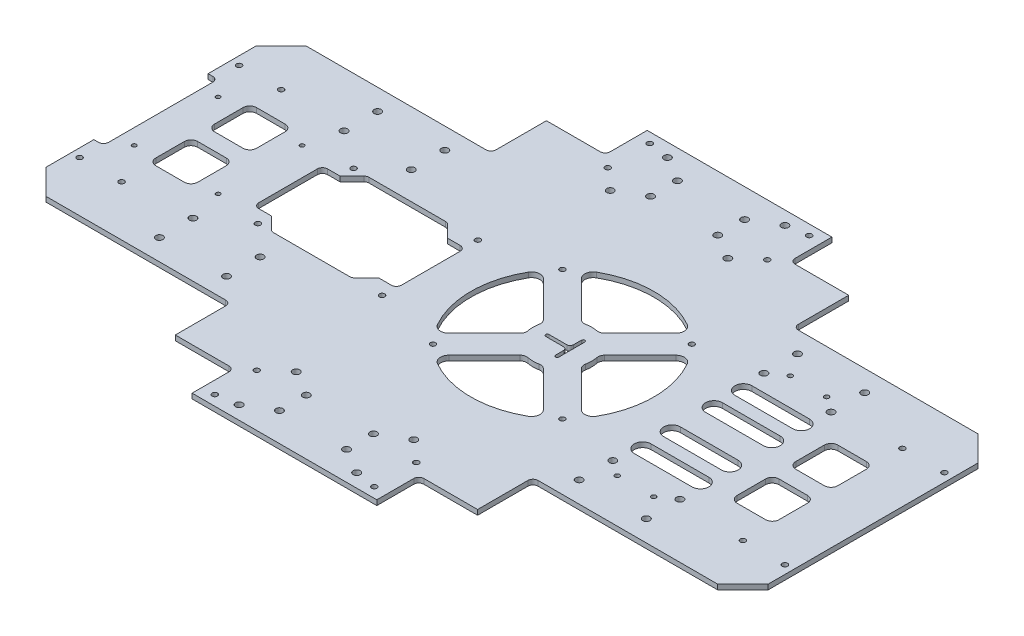
SolidWorks part; units mm, degrees
ref_plane "前视基准面" through (0, 0, 0) normal (0, 0, 1) x (1, 0, 0)
ref_plane "上视基准面" through (0, 0, 0) normal (0, 1, 0) x (1, 0, 0)
ref_plane "右视基准面" through (0, 0, 0) normal (1, 0, 0) x (0, 0, -1)
sketch "草图1" plane through (0, 0, 0) normal (0, 1, 0) x (1, 0, 0)
  line L0 (-82.9301, 135.4999) -> (-82.9301, 112.4999)
  line L1 (77.0699, 77.4999) -> (77.0699, -77.4999)
  line L2 (-47.9301, 77.4999) -> (77.0699, 77.4999)
  line L3 (-137.9301, 0) -> (-352.9301, 0) construction
  line L4 (-47.9301, -77.4999) -> (77.0699, -77.4999)
  line L5 (-137.9301, 112.4999) -> (-137.9301, -112.4999) construction
  line L6 (-137.9301, 0) -> (77.0699, 0) construction
  line L7 (-227.9301, -77.4999) -> (-352.9301, -77.4999)
  line L8 (-82.9301, 135.4999) -> (-192.9301, 135.4999)
  line L9 (-192.9301, 135.4999) -> (-192.9301, 112.4999)
  line L10 (-192.9301, -135.4999) -> (-82.9301, -135.4999)
  line L11 (-82.9301, -135.4999) -> (-82.9301, -112.4999)
  line L12 (-47.9301, 112.4999) -> (-47.9301, 77.4999)
  line L13 (-227.9301, 77.4999) -> (-352.9301, 77.4999)
  line L14 (-352.9301, 77.4999) -> (-352.9301, -77.4999)
  line L15 (-192.9301, -112.4999) -> (-192.9301, -135.4999)
  line L16 (-47.9301, -112.4999) -> (-82.9301, -112.4999)
  line L17 (-47.9301, 112.4999) -> (-82.9301, 112.4999)
  line L18 (-47.9301, -112.4999) -> (-47.9301, -77.4999)
  line L19 (-227.9301, -112.4999) -> (-227.9301, -77.4999)
  line L20 (-227.9301, -112.4999) -> (-192.9301, -112.4999)
  line L21 (-227.9301, 112.4999) -> (-192.9301, 112.4999)
  line L22 (-227.9301, 112.4999) -> (-227.9301, 77.4999)
  point P7 (77.0699, 0)
extrude "凸台-拉伸1" add sketch "草图1" along normal blind 3
fillet "圆角1" radius 3 8 edges at (-227.9301, 1.5, -77.4999) (-192.9301, 1.5, -112.4999) (-227.9301, 1.5, 77.4999) (-192.9301, 1.5, 112.4999) (-82.9301, 1.5, 112.4999) (-47.9301, 1.5, 77.4999) (-47.9301, 1.5, -77.4999) (-82.9301, 1.5, -112.4999)
sketch "草图2" plane through (0, 3, 0) normal (0, 1, 0) x (1, 0, 0)
  line L0 (77.0699, 47.5) -> (72.0699, 47.5) construction
  line L1 (72.0699, 47.5) -> (47.0699, 47.5) construction
  line L2 (47.0699, 47.5) -> (47.0699, -47.5) construction
  line L3 (47.0699, -47.5) -> (72.0699, -47.5) construction
  line L4 (72.0699, -47.5) -> (72.0699, 47.5) construction
  line L5 (72.0699, -47.5) -> (77.0699, -47.5) construction
  line L6 (77.0699, 0) -> (-352.9301, 0) construction
  line L7 (77.0699, -77.4999) -> (77.0699, 77.4999) construction
  line L8 (-352.9301, 77.4999) -> (-352.9301, -77.4999) construction
  line L9 (77.0699, 47.5) -> (77.0699, -47.5) construction
  line L10 (-137.9301, 135.4999) -> (-137.9301, -135.4999) construction
  line L11 (-82.9301, 135.4999) -> (-192.9301, 135.4999) construction
  line L12 (-192.9301, -135.4999) -> (-82.9301, -135.4999) construction
  line L13 (-90.4301, 104.4999) -> (-90.4301, 129.4999) construction
  line L14 (-90.4301, 129.4999) -> (-90.4301, 135.4999) construction
  line L15 (-185.4301, 135.4999) -> (-185.4301, 129.4999) construction
  line L16 (-185.4301, 104.4999) -> (-90.4301, 104.4999) construction
  line L17 (-185.4301, 135.4999) -> (-90.4301, 135.4999) construction
  line L18 (-185.4301, 129.4999) -> (-185.4301, 104.4999) construction
  line L19 (-90.4301, 129.4999) -> (-185.4301, 129.4999) construction
  line L20 (-90.4301, -129.4999) -> (-185.4301, -129.4999) construction
  line L21 (-185.4301, -129.4999) -> (-185.4301, -104.4999) construction
  line L22 (-185.4301, -135.4999) -> (-90.4301, -135.4999) construction
  line L23 (-185.4301, -104.4999) -> (-90.4301, -104.4999) construction
  line L24 (-185.4301, -135.4999) -> (-185.4301, -129.4999) construction
  line L25 (-90.4301, -129.4999) -> (-90.4301, -135.4999) construction
  line L26 (-90.4301, -104.4999) -> (-90.4301, -129.4999) construction
  line L27 (-352.9301, 47.5) -> (-352.9301, -47.5) construction
  line L28 (-347.9301, -47.5) -> (-352.9301, -47.5) construction
  line L29 (-347.9301, -47.5) -> (-347.9301, 47.5) construction
  line L30 (-322.9301, -47.5) -> (-347.9301, -47.5) construction
  line L31 (-322.9301, 47.5) -> (-322.9301, -47.5) construction
  line L32 (-347.9301, 47.5) -> (-322.9301, 47.5) construction
  line L33 (-352.9301, 47.5) -> (-347.9301, 47.5) construction
  circle A0 centre (47.0699, 47.5) radius 1.6
  circle A1 centre (72.0699, 47.5) radius 1.6
  circle A2 centre (47.0699, -47.5) radius 1.6
  circle A3 centre (72.0699, -47.5) radius 1.6
  circle A4 centre (-185.4301, 104.4999) radius 1.6
  circle A5 centre (-90.4301, 129.4999) radius 1.6
  circle A6 centre (-90.4301, 104.4999) radius 1.6
  circle A7 centre (-185.4301, 129.4999) radius 1.6
  circle A8 centre (-185.4301, -129.4999) radius 1.6
  circle A9 centre (-90.4301, -104.4999) radius 1.6
  circle A10 centre (-90.4301, -129.4999) radius 1.6
  circle A11 centre (-185.4301, -104.4999) radius 1.6
  circle A12 centre (-347.9301, -47.5) radius 1.6
  circle A13 centre (-322.9301, -47.5) radius 1.6
  circle A14 centre (-347.9301, 47.5) radius 1.6
  circle A15 centre (-322.9301, 47.5) radius 1.6
extrude "切除-拉伸1" cut sketch "草图2" against normal blind 47
sketch "草图3" plane through (0, 3, 0) normal (0, 1, 0) x (1, 0, 0)
  line L0 (-137.9301, 135.4999) -> (-137.9301, -135.4999) construction
  line L1 (-82.9301, 135.4999) -> (-192.9301, 135.4999) construction
  line L2 (-192.9301, -135.4999) -> (-82.9301, -135.4999) construction
  line L3 (-137.9301, 0) -> (-262.9301, 0) construction
  line L4 (-137.9301, 0) -> (-12.9301, 0) construction
  line L5 (-262.9301, 0) -> (-262.9301, 55) construction
  line L6 (-12.9301, -34) -> (-12.9301, 34) construction
  line L7 (-12.9301, 0) -> (-12.9301, 62) construction
  line L8 (-12.9301, 0) -> (-12.9301, -62) construction
  line L9 (-282.9301, -45) -> (-242.9301, -65) construction
  line L10 (-282.9301, 65) -> (-242.9301, 65) construction
  line L11 (-282.9301, 65) -> (-282.9301, 45) construction
  line L12 (-282.9301, 45) -> (-242.9301, 45) construction
  line L13 (-242.9301, 65) -> (-242.9301, 45) construction
  line L14 (-282.9301, 65) -> (-242.9301, 45) construction
  line L15 (-282.9301, 45) -> (-242.9301, 65) construction
  line L16 (-282.9301, -65) -> (-242.9301, -45) construction
  line L17 (-242.9301, -65) -> (-242.9301, -45) construction
  line L18 (-282.9301, -45) -> (-242.9301, -45) construction
  line L19 (-282.9301, -65) -> (-282.9301, -45) construction
  line L20 (-282.9301, -65) -> (-242.9301, -65) construction
  line L21 (7.0699, -65) -> (-32.9301, -65) construction
  line L22 (7.0699, -65) -> (7.0699, -45) construction
  line L23 (7.0699, -45) -> (-32.9301, -45) construction
  line L24 (-32.9301, -65) -> (-32.9301, -45) construction
  line L25 (7.0699, -65) -> (-32.9301, -45) construction
  line L26 (7.0699, 45) -> (-32.9301, 65) construction
  line L27 (7.0699, 65) -> (-32.9301, 45) construction
  line L28 (-32.9301, 65) -> (-32.9301, 45) construction
  line L29 (7.0699, 45) -> (-32.9301, 45) construction
  line L30 (7.0699, 65) -> (7.0699, 45) construction
  line L31 (7.0699, 65) -> (-32.9301, 65) construction
  line L32 (7.0699, -45) -> (-32.9301, -65) construction
  line L33 (-12.9301, 0) -> (-12.9301, -62) construction
  line L34 (-12.9301, 0) -> (-12.9301, 55) construction
  line L35 (-337.9301, 25) -> (-337.9301, -25) construction
  line L36 (-23.767, 51.5) -> (-12.9301, 34) construction
  line L37 (-352.9301, 77.4999) -> (-352.9301, -77.4999) construction
  line L38 (-23.767, 51.5) -> (-2.0931, 51.5) construction
  line L39 (-12.9301, 34) -> (-2.0931, 51.5) construction
  line L40 (-12.9301, -34) -> (-23.767, -51.5) construction
  line L41 (-23.767, -51.5) -> (-2.0931, -51.5) construction
  line L42 (-2.0931, -51.5) -> (-12.9301, -34) construction
  line L43 (-30.1258, 30) -> (4.2656, 30) construction
  line L44 (-30.1258, 35) -> (4.2656, 35)
  line L45 (-30.1258, 25) -> (-12.9301, 25)
  line L46 (-30.1258, 12.5) -> (4.2656, 12.5) construction
  line L47 (-30.1258, 17.5) -> (4.2656, 17.5)
  line L48 (-30.1258, 7.5) -> (4.2656, 7.5)
  line L49 (-30.1258, -30) -> (4.2656, -30) construction
  line L50 (-30.1258, -35) -> (4.2656, -35)
  line L51 (-30.1258, -25) -> (4.2656, -25)
  line L52 (-30.1258, -12.5) -> (4.2656, -12.5) construction
  line L53 (-30.1258, -17.5) -> (4.2656, -17.5)
  line L54 (-30.1258, -7.5) -> (4.2656, -7.5)
  line L55 (-8.9301, 25) -> (4.2656, 25)
  line L57 (-12.9301, 25) -> (-8.9301, 25)
  line L60 (-16.9301, -35) -> (-8.9301, 35) construction
  line L61 (-16.9301, 35) -> (-8.9301, -35) construction
  circle A0 centre (-282.9301, 65) radius 2.1
  circle A1 centre (-282.9301, 45) radius 2.1
  circle A2 centre (-242.9301, 65) radius 2.1
  circle A3 centre (-242.9301, 45) radius 2.1
  circle A4 centre (-242.9301, -45) radius 2.1
  circle A5 centre (-242.9301, -65) radius 2.1
  circle A6 centre (-282.9301, -45) radius 2.1
  circle A7 centre (-282.9301, -65) radius 2.1
  circle A8 centre (7.0699, -65) radius 2.1
  circle A9 centre (7.0699, -45) radius 2.1
  circle A10 centre (-32.9301, -65) radius 2.1
  circle A11 centre (-32.9301, -45) radius 2.1
  circle A12 centre (-32.9301, 45) radius 2.1
  circle A13 centre (-32.9301, 65) radius 2.1
  circle A14 centre (7.0699, 45) radius 2.1
  circle A15 centre (7.0699, 65) radius 2.1
  circle A16 centre (-23.767, -51.5) radius 1.4
  circle A17 centre (-2.0931, -51.5) radius 1.4
  arc A18 (-30.1258, 35) -> (-30.1258, 25) centre (-30.1258, 30) ccw
  circle A19 centre (-23.767, 51.5) radius 1.4
  arc A20 (4.2656, 25) -> (4.2656, 35) centre (4.2656, 30) ccw
  circle A21 centre (-2.0931, 51.5) radius 1.4
  circle A22 centre (-337.9301, 25) radius 1.25
  circle A23 centre (-287.9301, 25) radius 1.25
  circle A24 centre (-287.9301, -25) radius 1.25
  circle A25 centre (-337.9301, -25) radius 1.25
  arc A26 (-30.1258, 17.5) -> (-30.1258, 7.5) centre (-30.1258, 12.5) ccw
  arc A27 (4.2656, 7.5) -> (4.2656, 17.5) centre (4.2656, 12.5) ccw
  arc A28 (-30.1258, -35) -> (-30.1258, -25) centre (-30.1258, -30) cw
  arc A29 (4.2656, -25) -> (4.2656, -35) centre (4.2656, -30) cw
  arc A30 (-30.1258, -17.5) -> (-30.1258, -7.5) centre (-30.1258, -12.5) cw
  arc A31 (4.2656, -7.5) -> (4.2656, -17.5) centre (4.2656, -12.5) cw
  point P66 (-352.9301, 0)
  point P68 (-12.9301, 30)
  point P76 (-12.9301, 12.5)
  point P83 (-12.9301, -30)
  point P90 (-12.9301, -12.5)
  dimension "D9" = 15
  dimension "D11" = 5
  dimension "D1" = 125
  dimension "D2" = 50
  dimension "D3" = 55
  dimension "D4" = 50
  dimension "D5" = 50
  dimension "D6" = 50
  dimension "D7" = 40
  dimension "D8" = 20
  dimension "D10" = 0
  dimension "D12" = 30
  dimension "D13" = 7.5
  dimension "D14" = 34.3914
extrude "切除-拉伸2" cut sketch "草图3" against normal blind 47
chamfer "倒角1" distance 15 angle 45 4 edges at (77.0699, 1.5, -77.4999) (77.0699, 1.5, 77.4999) (-352.9301, 1.5, 77.4999) (-352.9301, 1.5, -77.4999)
sketch "草图5" plane through (0, 3, 0) normal (0, 1, 0) x (1, 0, 0)
  line L0 (-68.5001, 28.1163) -> (-89.6587, 6.9576)
  line L1 (-89.6587, -6.9576) -> (-68.5001, -28.1163)
  line L2 (-79.8138, -39.43) -> (-100.9725, -18.2713)
  line L3 (-114.8877, -18.2713) -> (-136.0464, -39.43)
  line L4 (-147.3601, -28.1163) -> (-126.2014, -6.9576)
  line L5 (-126.2014, 6.9576) -> (-147.3601, 28.1163)
  line L6 (-136.0464, 39.43) -> (-114.8877, 18.2713)
  line L7 (-100.9725, 18.2713) -> (-79.8138, 39.43)
  line L8 (-102.3298, -7.7031) -> (-102.3298, 7.7679)
  line L9 (-104.3298, -2.9676) -> (-104.3298, -7.7031)
  line L10 (-104.3298, 7.7679) -> (-104.3298, 3.0324)
  line L11 (-116.9301, -0.9676) -> (-106.3298, -0.9676)
  line L12 (-106.3298, 1.0324) -> (-116.9301, 1.0324)
  line L13 (-352.9301, 0) -> (77.0699, 0) construction
  line L14 (-352.9301, 62.4999) -> (-352.9301, -62.4999) construction
  line L15 (77.0699, -62.4999) -> (77.0699, 62.4999) construction
  line L16 (-137.9301, -135.4999) -> (-137.9301, -67.6391) construction
  line L17 (-192.9301, -135.4999) -> (-82.9301, -135.4999) construction
  line L18 (-137.9301, -67.6391) -> (-107.9301, -67.6391) construction
  line L19 (-107.9301, -67.6391) -> (-107.9301, 0) construction
  circle A0 centre (-69.3928, 38.5373) radius 1.55
  circle A1 centre (-69.3928, -38.5373) radius 1.55
  circle A2 centre (-146.4674, -38.5373) radius 1.55
  circle A3 centre (-146.4674, 38.5373) radius 1.55
  arc A4 (-60.6246, -27.0637) -> (-60.6246, 27.0637) centre (-107.9301, 0) ccw
  arc A5 (-60.6246, 27.0637) -> (-68.5001, 28.1163) centre (-64.9645, 24.5808) ccw
  arc A6 (-89.6587, 6.9576) -> (-90.7559, 3.361) centre (-86.8303, 4.1292) ccw
  arc A7 (-90.7559, -3.361) -> (-90.7559, 3.361) centre (-107.9301, 0) ccw
  arc A8 (-90.7559, -3.361) -> (-89.6587, -6.9576) centre (-86.8303, -4.1292) ccw
  arc A9 (-68.5001, -28.1163) -> (-60.6246, -27.0637) centre (-64.9645, -24.5808) ccw
  arc A10 (-80.8664, -47.3055) -> (-79.8138, -39.43) centre (-83.3493, -42.9655) ccw
  arc A11 (-134.9937, -47.3055) -> (-80.8664, -47.3055) centre (-107.9301, 0) ccw
  arc A12 (-100.9725, -18.2713) -> (-104.5691, -17.1742) centre (-103.8009, -21.0998) ccw
  arc A13 (-111.291, -17.1742) -> (-104.5691, -17.1742) centre (-107.9301, 0) ccw
  arc A14 (-111.291, -17.1742) -> (-114.8877, -18.2713) centre (-112.0593, -21.0998) ccw
  arc A15 (-136.0464, -39.43) -> (-134.9937, -47.3055) centre (-132.5108, -42.9655) ccw
  arc A16 (-126.2014, -6.9576) -> (-125.1043, -3.361) centre (-129.0298, -4.1292) ccw
  arc A17 (-125.1043, 3.361) -> (-125.1043, -3.361) centre (-107.9301, 0) ccw
  arc A18 (-125.1043, 3.361) -> (-126.2014, 6.9576) centre (-129.0298, 4.1292) ccw
  arc A19 (-147.3601, 28.1163) -> (-155.2356, 27.0637) centre (-150.8956, 24.5808) ccw
  arc A20 (-155.2356, 27.0637) -> (-155.2356, -27.0637) centre (-107.9301, 0) ccw
  arc A21 (-155.2356, -27.0637) -> (-147.3601, -28.1163) centre (-150.8956, -24.5808) ccw
  arc A22 (-104.5691, 17.1742) -> (-111.291, 17.1742) centre (-107.9301, 0) ccw
  arc A23 (-114.8877, 18.2713) -> (-111.291, 17.1742) centre (-112.0593, 21.0998) ccw
  arc A24 (-104.5691, 17.1742) -> (-100.9725, 18.2713) centre (-103.8009, 21.0998) ccw
  arc A25 (-79.8138, 39.43) -> (-80.8664, 47.3055) centre (-83.3493, 42.9655) ccw
  arc A26 (-80.8664, 47.3055) -> (-134.9937, 47.3055) centre (-107.9301, 0) ccw
  arc A27 (-134.9937, 47.3055) -> (-136.0464, 39.43) centre (-132.5108, 42.9655) ccw
  arc A28 (-102.3298, 7.7679) -> (-104.3298, 7.7679) centre (-103.3298, 7.7679) ccw
  arc A29 (-104.3298, -7.7031) -> (-102.3298, -7.7031) centre (-103.3298, -7.7031) ccw
  arc A30 (-106.3298, 1.0324) -> (-104.3298, 3.0324) centre (-106.3298, 3.0324) ccw
  arc A31 (-104.3298, -2.9676) -> (-106.3298, -0.9676) centre (-106.3298, -2.9676) ccw
  arc A32 (-116.9301, 1.0324) -> (-116.9301, -0.9676) centre (-116.9301, 0.0324) ccw
extrude "切除-拉伸3" cut sketch "草图5" against normal blind 47
sketch "草图6" plane through (0, 3, 0) normal (0, 1, 0) x (1, 0, 0)
  line L0 (-260.7825, 28.5) -> (-186.7825, 28.5) construction
  line L1 (-260.7825, 28.5) -> (-260.7825, -28.5) construction
  line L2 (-260.7825, -28.5) -> (-186.7825, -28.5) construction
  line L3 (-186.7825, 28.5) -> (-186.7825, -28.5) construction
  line L4 (-352.9301, 0) -> (77.0699, 0) construction
  line L5 (-352.9301, 62.4999) -> (-352.9301, -62.4999) construction
  line L6 (77.0699, -62.4999) -> (77.0699, 62.4999) construction
  line L7 (-270.2825, -20.5) -> (-260.7825, -20.5)
  line L8 (-186.2825, -19.5) -> (-186.2825, 19.5)
  line L9 (-187.2825, 20.5) -> (-196.7825, 20.5)
  line L10 (-271.2825, 19.5) -> (-271.2825, -19.5)
  line L11 (-251.2825, -28.5) -> (-251.2825, -24.9) construction
  line L12 (-251.2825, -24.9) -> (-213.2825, -24.9) construction
  line L13 (-213.2825, -24.9) -> (-213.2825, -23.5) construction
  line L14 (-213.2825, -23.5) -> (-193.2825, -23.5) construction
  line L15 (-190.2825, -26.5) -> (-190.2825, -28.5) construction
  line L16 (-183.2825, -28.5) -> (-183.2825, 28.5) construction
  line L17 (-190.2825, 28.5) -> (-190.2825, 26.5) construction
  line L18 (-193.2825, 23.5) -> (-213.2825, 23.5) construction
  line L19 (-213.2825, 23.5) -> (-213.2825, 24.9) construction
  line L20 (-213.2825, 24.9) -> (-251.2825, 24.9) construction
  line L21 (-251.2825, 24.9) -> (-251.2825, 28.5) construction
  line L22 (-251.2825, 28.5) -> (-253.9086, 28.5) construction
  line L23 (-264.2825, 28.5) -> (-264.2825, 27.5) construction
  line L24 (-268.2825, 23.5) -> (-274.2825, 23.5) construction
  line L25 (-274.2825, 23.5) -> (-274.2825, -23.5) construction
  line L26 (-274.2825, -23.5) -> (-268.2825, -23.5) construction
  line L27 (-264.2825, -27.5) -> (-264.2825, -28.5) construction
  line L28 (-253.9086, -28.5) -> (-251.2825, -28.5) construction
  line L29 (-270.2825, 20.5) -> (-271.2825, 20.5)
  line L30 (-271.2825, 20.5) -> (-271.2825, 19.5)
  line L31 (-271.2825, -19.5) -> (-271.2825, -20.5)
  line L32 (-271.2825, -20.5) -> (-270.2825, -20.5)
  line L33 (-187.2825, -20.5) -> (-186.2825, -20.5)
  line L34 (-186.2825, -20.5) -> (-186.2825, -19.5)
  line L35 (-187.2825, 20.5) -> (-186.2825, 20.5)
  line L36 (-186.2825, 20.5) -> (-186.2825, 19.5)
  line L37 (-162.4301, 0) -> (-183.2825, 0) construction
  line L38 (-183.2825, 0) -> (-183.2825, 23.5) construction
  line L39 (-228.7825, 20.5) -> (-228.7825, 28.5) construction
  line L40 (-252.7825, 28.5) -> (-204.7825, 28.5)
  line L41 (-204.7825, 28.5) -> (-196.7825, 20.5)
  line L42 (-252.7825, 28.5) -> (-260.7825, 20.5)
  line L43 (-260.7825, 20.5) -> (-270.2825, 20.5)
  line L44 (-252.7825, -28.5) -> (-260.7825, -20.5)
  line L45 (-252.7825, -28.5) -> (-204.7825, -28.5)
  line L46 (-204.7825, -28.5) -> (-196.7825, -20.5)
  line L47 (-196.7825, -20.5) -> (-187.2825, -20.5)
  circle A0 centre (-260.7825, 28.5) radius 1.6
  circle A1 centre (-186.7825, 28.5) radius 1.6
  circle A2 centre (-260.7825, -28.5) radius 1.6
  circle A3 centre (-186.7825, -28.5) radius 1.6
  circle A4 centre (-186.7825, -28.5) radius 1.5 construction
  arc A5 (-190.2825, -26.5) -> (-193.2825, -23.5) centre (-193.2825, -26.5) ccw construction
  arc A6 (-190.2825, -28.5) -> (-183.2825, -28.5) centre (-186.7825, -28.5) ccw construction
  arc A7 (-183.2825, 28.5) -> (-190.2825, 28.5) centre (-186.7825, 28.5) ccw construction
  arc A8 (-193.2825, 23.5) -> (-190.2825, 26.5) centre (-193.2825, 26.5) ccw construction
  arc A9 (-257.9521, 30.5588) -> (-253.9086, 28.5) centre (-253.9086, 33.5) ccw construction
  arc A10 (-257.9521, 30.5588) -> (-264.2825, 28.5) centre (-260.7825, 28.5) ccw construction
  arc A11 (-268.2825, 23.5) -> (-264.2825, 27.5) centre (-268.2825, 27.5) ccw construction
  arc A12 (-264.2825, -27.5) -> (-268.2825, -23.5) centre (-268.2825, -27.5) ccw construction
  arc A13 (-264.2825, -28.5) -> (-257.9521, -30.5588) centre (-260.7825, -28.5) ccw construction
  arc A14 (-253.9086, -28.5) -> (-257.9521, -30.5588) centre (-253.9086, -33.5) ccw construction
  arc A15 (-155.2356, 27.0637) -> (-155.2356, -27.0637) centre (-107.9301, 0) ccw construction
  dimension "D1" = 3.2
  dimension "D2" = 3.2
  dimension "D3" = 3.2
  dimension "D4" = 3.2
extrude "切除-拉伸4" cut sketch "草图6" against normal blind 47
fillet "圆角2" radius 3 8 edges at (-204.7825, 1.5, 28.5) (-252.7825, 1.5, 28.5) (-271.2825, 1.5, 20.5) (-186.2825, 1.5, 20.5) (-186.2825, 1.5, -20.5) (-271.2825, 1.5, -20.5) (-204.7825, 1.5, -28.5) (-252.7825, 1.5, -28.5)
sketch "草图7" plane through (0, 3, 0) normal (0, 1, 0) x (1, 0, 0)
  line L1 (-337.9301, 25) -> (-337.9301, -25) construction
  line L2 (-337.9301, 0) -> (-347.1301, 0) construction
  line L3 (-347.1301, 0) -> (-347.1301, 34)
  line L4 (-347.1301, 0) -> (-347.1301, -34)
  line L5 (-347.1301, -34) -> (-352.9301, -34)
  line L6 (-352.9301, 62.4999) -> (-352.9301, -62.4999) construction
  line L7 (-347.1301, 34) -> (-352.9301, 34)
  line L8 (-352.9301, 34) -> (-352.9301, -34)
extrude "切除-拉伸5" cut sketch "草图7" against normal blind 47
fillet "圆角3" radius 3 2 edges at (-347.1301, 1.5, 34) (-347.1301, 1.5, -34)
sketch "草图8" plane through (0, 3, 0) normal (0, 1, 0) x (1, 0, 0)
  line L0 (-347.1301, 0) -> (-312.1301, 0)
  line L1 (77.0699, 0) -> (32.0699, 0) construction
  line L2 (-347.1301, -31) -> (-347.1301, 31) construction
  line L3 (-335.3508, 26.6608) -> (-288.9094, -26.6608) construction
  line L4 (-300.0305, -8.0391) -> (-300.0305, -25.0391)
  line L5 (-325.0305, -8.0391) -> (-325.0305, -25.0391)
  line L6 (-325.0305, 30.9609) -> (-300.0305, -29.0391) construction
  line L7 (-300.0305, 9.9609) -> (-300.0305, 26.9609)
  line L8 (77.0699, -62.4999) -> (77.0699, 62.4999) construction
  line L11 (47.0699, 9) -> (47.0699, 26)
  line L12 (26.0699, 5) -> (43.0699, 5)
  line L14 (26.0699, 30) -> (43.0699, 30)
  line L15 (22.0699, 9) -> (22.0699, 26)
  line L16 (22.0699, -9) -> (22.0699, -26)
  line L17 (26.0699, -30) -> (43.0699, -30)
  line L18 (26.0699, -5) -> (43.0699, -5)
  line L19 (47.0699, -9) -> (47.0699, -26)
  line L20 (-321.0305, 30.9609) -> (-304.0305, 30.9609)
  line L21 (-321.0305, 5.9609) -> (-304.0305, 5.9609)
  line L22 (-324.3388, -31.2402) -> (-300.0305, 30.9609) construction
  line L23 (-325.0305, 9.9609) -> (-325.0305, 26.9609)
  line L24 (-321.0305, -4.0391) -> (-304.0305, -4.0391)
  line L25 (-321.0305, -29.0391) -> (-304.0305, -29.0391)
  arc A0 (22.0699, -26) -> (26.0699, -30) centre (26.0699, -26) ccw
  arc A1 (43.0699, -30) -> (47.0699, -26) centre (43.0699, -26) ccw
  arc A2 (47.0699, -9) -> (43.0699, -5) centre (43.0699, -9) ccw
  arc A3 (26.0699, -5) -> (22.0699, -9) centre (26.0699, -9) ccw
  arc A4 (26.0699, 5) -> (22.0699, 9) centre (26.0699, 9) cw
  arc A5 (43.0699, 5) -> (47.0699, 9) centre (43.0699, 9) ccw
  arc A6 (47.0699, 26) -> (43.0699, 30) centre (43.0699, 26) ccw
  arc A7 (22.0699, 26) -> (26.0699, 30) centre (26.0699, 26) cw
  arc A8 (-300.0305, 26.9609) -> (-304.0305, 30.9609) centre (-304.0305, 26.9609) ccw
  arc A9 (-321.0305, -4.0391) -> (-325.0305, -8.0391) centre (-321.0305, -8.0391) ccw
  arc A10 (-325.0305, -25.0391) -> (-321.0305, -29.0391) centre (-321.0305, -25.0391) ccw
  arc A11 (-325.0305, 26.9609) -> (-321.0305, 30.9609) centre (-321.0305, 26.9609) cw
  arc A12 (-321.0305, 5.9609) -> (-325.0305, 9.9609) centre (-321.0305, 9.9609) cw
  arc A13 (-304.0305, -29.0391) -> (-300.0305, -25.0391) centre (-304.0305, -25.0391) ccw
  arc A14 (-304.0305, 5.9609) -> (-300.0305, 9.9609) centre (-304.0305, 9.9609) ccw
  arc A15 (-300.0305, -8.0391) -> (-304.0305, -4.0391) centre (-304.0305, -8.0391) ccw
  point P8 (-312.1301, 0)
  point P16 (34.9703, -0.9609)
  point P28 (22.0699, -30)
  point P34 (47.0699, -5)
  point P37 (22.0699, -5)
  point P40 (22.0699, 5)
  point P43 (47.0699, 5)
  dimension "D3" = 4
  dimension "D2" = 4
  dimension "D1" = 25
extrude "切除-拉伸6" cut sketch "草图8" against normal blind 47 contours L21 A14 L7 A8 L20 A11 L23 A12 | L4 A15 L24 A9 L5 A10 L25 A13 | A7 L15 A4 L12 A5 L11 A6 L14 | L18 A3 L16 A0 L17 A1 L19 A2
sketch "草图9" plane through (0, 3, 0) normal (0, 1, 0) x (1, 0, 0)
  line L0 (-137.9301, 135.4999) -> (-137.9301, 0) construction
  line L1 (-227.9301, 112.4999) -> (-198.5667, 112.4999)
  line L2 (-227.9301, 112.4999) -> (-227.9301, 110.4999)
  line L3 (-227.9301, 110.4999) -> (-192.9301, 110.4999)
  line L4 (-192.9301, 112.4999) -> (-192.9301, 110.4999)
  line L5 (-82.9301, 135.4999) -> (-192.9301, 135.4999) construction
  line L6 (-137.9301, 0) -> (77.0699, 0) construction
  line L7 (77.0699, -62.4999) -> (77.0699, 62.4999) construction
  line L8 (-192.9301, 112.4999) -> (-192.9301, 116.7715)
  line L9 (-192.9301, 116.7715) -> (-197.0435, 116.7715)
  line L10 (-197.0435, 116.7715) -> (-198.5667, 112.4999)
  line L11 (-78.8166, 116.7715) -> (-77.2934, 112.4999)
  line L12 (-82.9301, 116.7715) -> (-78.8166, 116.7715)
  line L13 (-82.9301, 112.4999) -> (-82.9301, 116.7715)
  line L14 (-82.9301, 112.4999) -> (-82.9301, 110.4999)
  line L15 (-47.9301, 110.4999) -> (-82.9301, 110.4999)
  line L16 (-47.9301, 112.4999) -> (-47.9301, 110.4999)
  line L17 (-47.9301, 112.4999) -> (-77.2934, 112.4999)
  line L18 (-47.9301, -112.4999) -> (-77.2934, -112.4999)
  line L19 (-47.9301, -112.4999) -> (-47.9301, -110.4999)
  line L20 (-47.9301, -110.4999) -> (-82.9301, -110.4999)
  line L21 (-82.9301, -112.4999) -> (-82.9301, -110.4999)
  line L22 (-82.9301, -112.4999) -> (-82.9301, -116.7715)
  line L23 (-82.9301, -116.7715) -> (-78.8166, -116.7715)
  line L24 (-78.8166, -116.7715) -> (-77.2934, -112.4999)
  line L25 (-197.0435, -116.7715) -> (-198.5667, -112.4999)
  line L26 (-192.9301, -116.7715) -> (-197.0435, -116.7715)
  line L27 (-192.9301, -112.4999) -> (-192.9301, -116.7715)
  line L28 (-192.9301, -112.4999) -> (-192.9301, -110.4999)
  line L29 (-227.9301, -110.4999) -> (-192.9301, -110.4999)
  line L30 (-227.9301, -112.4999) -> (-227.9301, -110.4999)
  line L31 (-227.9301, -112.4999) -> (-198.5667, -112.4999)
  dimension "D1" = 2
extrude "切除-拉伸7" cut sketch "草图9" against normal blind 10
fillet "圆角4" radius 3 4 edges at (-192.9301, 1.5, 110.4999) (-82.9301, 1.5, 110.4999) (-82.9301, 1.5, -110.4999) (-192.9301, 1.5, -110.4999)
sketch "草图10" plane through (0, 3, 0) normal (0, 1, 0) x (1, 0, 0)
  line L0 (-195.9301, 110.4999) -> (-79.9301, 110.4999) construction
  line L1 (-347.1301, 0) -> (77.0699, 0) construction
  line L2 (-82.9301, 135.4999) -> (-192.9301, 135.4999) construction
  line L3 (-137.9301, 135.4999) -> (-137.9301, 110.4999) construction
  line L4 (-347.1301, -31) -> (-347.1301, 31) construction
  line L5 (77.0699, -62.4999) -> (77.0699, 62.4999) construction
  line L6 (-137.9301, -135.4999) -> (-137.9301, -110.4999) construction
  line L7 (-195.9301, -110.4999) -> (-79.9301, -110.4999) construction
  circle A0 centre (-172.9301, 127.4999) radius 2.1
  circle A1 centre (-157.9301, 118.4999) radius 2.1
  circle A2 centre (-117.9301, 118.4999) radius 2.1
  circle A3 centre (-102.9301, 127.4999) radius 2.1
  circle A4 centre (-102.9301, -127.4999) radius 2.1
  circle A5 centre (-117.9301, -118.4999) radius 2.1
  circle A6 centre (-157.9301, -118.4999) radius 2.1
  circle A7 centre (-172.9301, -127.4999) radius 2.1
  dimension "D1" = 8
  dimension "D2" = 8
  dimension "D3" = 35
  dimension "D4" = 20
extrude "切除-拉伸8" cut sketch "草图10" against normal blind 10
sketch "草图11" plane through (0, 3, 0) normal (0, 1, 0) x (1, 0, 0)
  line L0 (-195.9301, 110.4999) -> (-79.9301, 110.4999) construction
  line L1 (-271.2825, 0) -> (77.0699, 0) construction
  line L2 (-271.2825, 17.5) -> (-271.2825, -17.5) construction
  line L3 (77.0699, -62.4999) -> (77.0699, 62.4999) construction
  line L4 (-195.9301, -110.4999) -> (-79.9301, -110.4999) construction
  circle A0 centre (-172.9301, 127.4999) radius 2.1 construction
  circle A1 centre (-157.9301, 118.4999) radius 2.1 construction
  circle A2 centre (-117.9301, 118.4999) radius 2.1 construction
  circle A3 centre (-102.9301, 127.4999) radius 2.1 construction
  circle A4 centre (-172.9301, 127.4999) radius 2.1 construction
  circle A5 centre (-157.9301, 118.4999) radius 2.1 construction
  circle A6 centre (-117.9301, 118.4999) radius 2.1 construction
  circle A7 centre (-102.9301, 127.4999) radius 2.1 construction
  circle A8 centre (-102.9301, 93.4999) radius 2.1
  circle A9 centre (-117.9301, 102.4999) radius 2.1
  circle A10 centre (-157.9301, 102.4999) radius 2.1
  circle A11 centre (-172.9301, 93.4999) radius 2.1
  circle A12 centre (-172.9301, -93.4999) radius 2.1
  circle A13 centre (-157.9301, -102.4999) radius 2.1
  circle A14 centre (-117.9301, -102.4999) radius 2.1
  circle A15 centre (-102.9301, -93.4999) radius 2.1
extrude "切除-拉伸9" cut sketch "草图11" against normal blind 10
